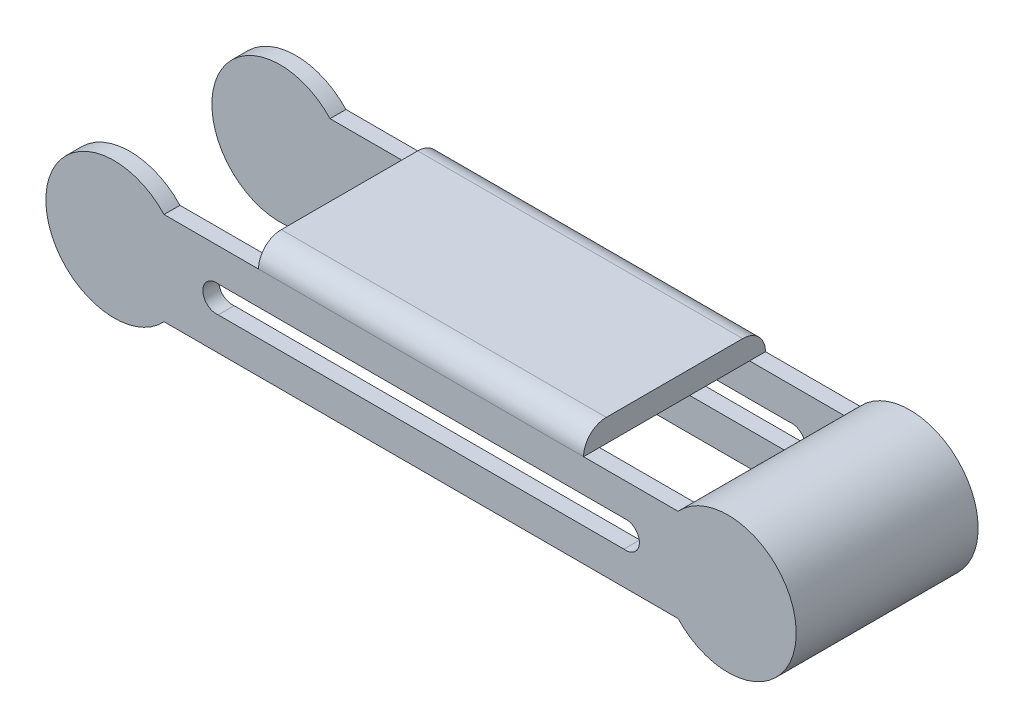
SolidWorks part; units mm, degrees
material "6061 Alloy"
ref_plane "Front Plane" through (0, 0, 0) normal (0, 0, 1) x (1, 0, 0)
ref_plane "Top Plane" through (0, 0, 0) normal (0, 1, 0) x (1, 0, 0)
ref_plane "Right Plane" through (0, 0, 0) normal (1, 0, 0) x (0, 0, -1)
sketch "Sketch1" plane through (0, 0, 0) normal (0, 0, 1) x (1, 0, 0)
  line L0 (-67.5, 0) -> (67.5, 0) construction
  line L2 (-56.5129, 10.2119) -> (56.5129, 10.2119)
  line L4 (-56.5129, -10.2119) -> (56.5129, -10.2119)
  line L6 (-56.5129, 10.2119) -> (56.5129, -10.2119) construction
  line L7 (-56.5129, -10.2119) -> (56.5129, 10.2119) construction
  arc A0 (-56.5129, 10.2119) -> (-56.5129, -10.2119) centre (-67.5, 0) ccw
  arc A1 (56.5129, -10.2119) -> (56.5129, 10.2119) centre (67.5, 0) ccw
  point P5 (0, 0)
  dimension "D1" = 15
  dimension "D2" = 15
  dimension "D3" = 135
  dimension "D4" = 10.2119
extrude "Boss-Extrude1" add sketch "Sketch1" along normal blind 40
ref_plane "Plane1" through (0, 0, 50) normal (0, 0, 1) x (1, 0, 0)
sketch "Sketch2" plane through (0, 0, 50) normal (0, 0, 1) x (1, 0, 0)
  line L0 (-45, 0) -> (45.0279, 0) construction
  line L2 (44.6061, 2.95) -> (-44.6061, 2.95)
  line L4 (44.6061, -2.95) -> (-44.6061, -2.95)
  line L6 (44.6061, 2.95) -> (-44.6061, -2.95) construction
  line L7 (44.6061, -2.95) -> (-44.6061, 2.95) construction
  arc A0 (-44.6061, 2.95) -> (-44.6061, -2.95) centre (-45, 0) ccw
  arc A1 (44.6061, -2.95) -> (44.6061, 2.95) centre (45.0279, 0) ccw
  point P5 (0, 0)
  dimension "D1" = 2.9762
  dimension "D2" = 2.98
  dimension "D4" = 45
  dimension "D3" = 5.9
extrude "Cut-Extrude1" cut sketch "Sketch2" against normal blind 60
sketch "Sketch3" plane through (0, 10.2119, 0) normal (0, 1, 0) x (1, 0, 0)
  line L0 (-56.5129, -20) -> (56.5129, -20) construction
  line L1 (-56.5129, -40) -> (-56.5129, 0) construction
  line L2 (56.5129, -40) -> (56.5129, 0) construction
  line L3 (0, 0) -> (0, -40) construction
  line L4 (56.5129, 0) -> (-56.5129, 0) construction
  line L5 (56.5129, -40) -> (-56.5129, -40) construction
  line L7 (-56.5129, -3.5) -> (56.5129, -3.5)
  line L8 (-56.5129, -3.5) -> (-56.5129, -36.5)
  line L9 (-56.5129, -36.5) -> (56.5129, -36.5)
  line L10 (56.5129, -3.5) -> (56.5129, -36.5)
  line L11 (-56.5129, -3.5) -> (56.5129, -36.5) construction
  line L12 (-56.5129, -36.5) -> (56.5129, -3.5) construction
  point P13 (0, -20)
  dimension "D1" = 33
extrude "Cut-Extrude2" cut sketch "Sketch3" against normal blind 25
ref_plane "Plane2" through (0, 10.2119, 0) normal (0, -1, 0) x (-1, 0, 0)
sketch "Sketch7" plane through (0, 10.2119, 0) normal (0, -1, 0) x (-1, 0, 0)
  line L0 (0, 0) -> (0, -40) construction
  line L1 (-56.5129, 0) -> (56.5129, 0) construction
  line L2 (-56.5129, -40) -> (56.5129, -40) construction
  line L3 (106.5129, -20) -> (56.5129, -20) construction
  line L4 (56.5129, -3.5) -> (56.5129, -36.5) construction
  line L6 (106.5129, -3.5) -> (56.5129, -3.5)
  line L7 (106.5129, -3.5) -> (106.5129, -36.5)
  line L8 (106.5129, -36.5) -> (56.5129, -36.5)
  line L9 (56.5129, -3.5) -> (56.5129, -36.5)
  line L10 (106.5129, -3.5) -> (56.5129, -36.5) construction
  line L11 (106.5129, -36.5) -> (56.5129, -3.5) construction
  point P10 (81.5129, -20)
  dimension "D1" = 50
extrude "Cut-Extrude6" cut sketch "Sketch7" against normal through all both and the other way through all
sketch "Sketch8" plane through (0, 10.2119, 0) normal (0, 1, 0) x (1, 0, 0)
  line L0 (0, 0) -> (0, -40) construction
  line L1 (56.5129, 0) -> (-56.5129, 0) construction
  line L2 (56.5129, -40) -> (-56.5129, -40) construction
  line L4 (-35.7371, 0) -> (35.7371, 0)
  line L5 (-35.7371, 0) -> (-35.7371, -40)
  line L6 (-35.7371, -40) -> (35.7371, -40)
  line L7 (35.7371, 0) -> (35.7371, -40)
  line L8 (-35.7371, 0) -> (35.7371, -40) construction
  line L9 (-35.7371, -40) -> (35.7371, 0) construction
  point P6 (0, -20)
extrude "Boss-Extrude2" add sketch "Sketch8" along normal blind 5
sketch "Sketch9" plane through (0, 0, 40) normal (0, 0, 1) x (1, 0, 0)
  line L0 (-35.7371, 10.2119) -> (35.7371, 10.2119)
split line "Split Line1"
sketch "Sketch10" plane through (0, 0, 0) normal (0, 0, -1) x (-1, 0, 0)
  line L0 (-35.7371, 10.2119) -> (35.7371, 10.2119)
split line "Split Line2"
fillet "Fillet1" radius 5 1 edges at (0, 15.2119, 40)
fillet "Fillet2" radius 5 1 edges at (0, 15.2119, 0)
